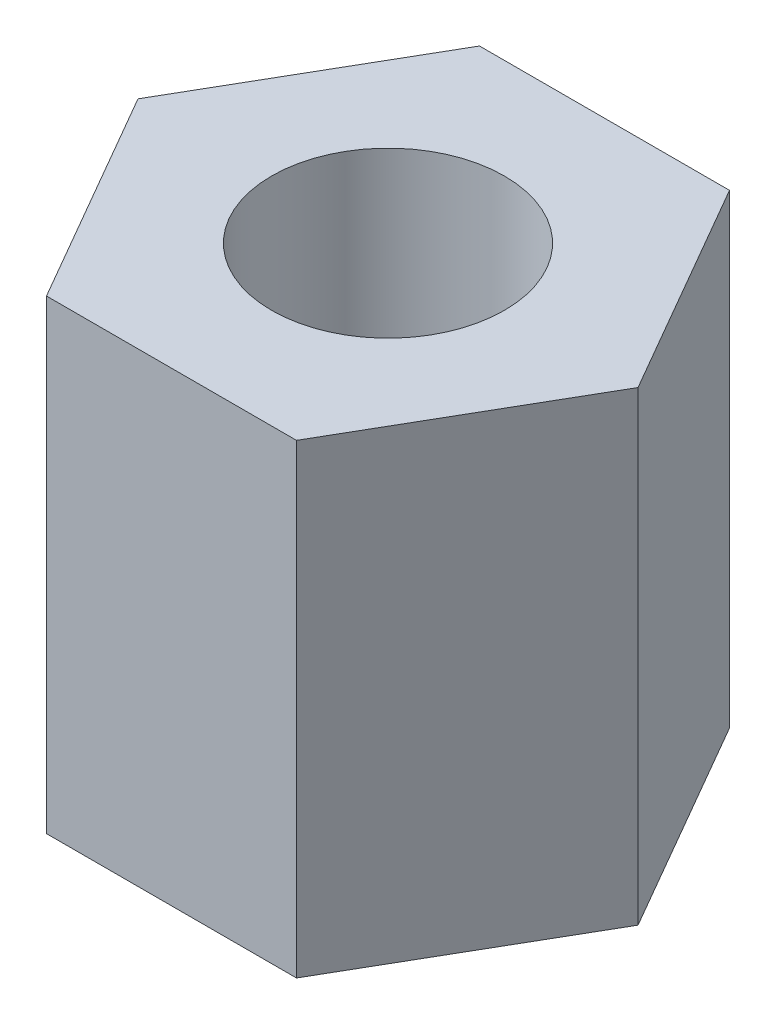
SolidWorks part; units mm, degrees
material "黄铜"
ref_plane "前视基准面" through (0, 0, 0) normal (0, 0, 1) x (1, 0, 0)
ref_plane "上视基准面" through (0, 0, 0) normal (0, 1, 0) x (1, 0, 0)
ref_plane "右视基准面" through (0, 0, 0) normal (1, 0, 0) x (0, 0, -1)
sketch "草图1" plane through (0, 0, 0) normal (0, 1, 0) x (1, 0, 0)
  line L1 (2.6847, 0) -> (1.3423, 2.325)
  line L2 (1.3423, 2.325) -> (-1.3423, 2.325)
  line L3 (-1.3423, 2.325) -> (-2.6847, 0)
  line L4 (-2.6847, 0) -> (-1.3423, -2.325)
  line L5 (-1.3423, -2.325) -> (1.3423, -2.325)
  line L6 (1.3423, -2.325) -> (2.6847, 0)
  circle A0 centre (0, 0) radius 2.325 construction
  dimension "D1" = 4.65
extrude "凸台-拉伸1" add sketch "草图1" along normal mid plane 5
hole_wizard "M3 螺纹孔1" positions "草图3" profile "草图2" tap size "M3" standard "GB"
sketch "草图3" plane through (0, -2.5, 0) normal (0, -1, 0) x (-1, 0, 0)
  point P0 (0, 0)
sketch "草图2" plane through (0, -2.5, 0) normal (1, 0, 0) x (0, 0, -1)
  line L0 (0, 0) -> (0, 8.2511)
  line L1 (0, 8.2511) -> (1.25, 7.5)
  line L2 (1.25, 7.5) -> (1.25, 0)
  line L5 (1.25, 0) -> (0, 0)
  line L10 (0, 8.2511) -> (-1.25, 7.5) construction
  line L11 (0, -6.35) -> (0, 107.95) construction
  dimension "螺纹孔钻头直径" = 2.5
  dimension "螺纹孔钻头深度" = 7.5
  dimension "导头角度" = 118
cosmetic thread "孔螺蚊线1" parameters "D1"=5, "D2"=3
mirror "镜向1" about plane through (0, 0, 0) normal (0, 1, 0) of "M3 螺纹孔1"
equation "\"高度\"= 5"
equation "\"对边距离\"= 4.65"
equation "\"D1@草图1\"=\"对边距离\""
equation "\"D1@凸台-拉伸1\"=\"高度\""
